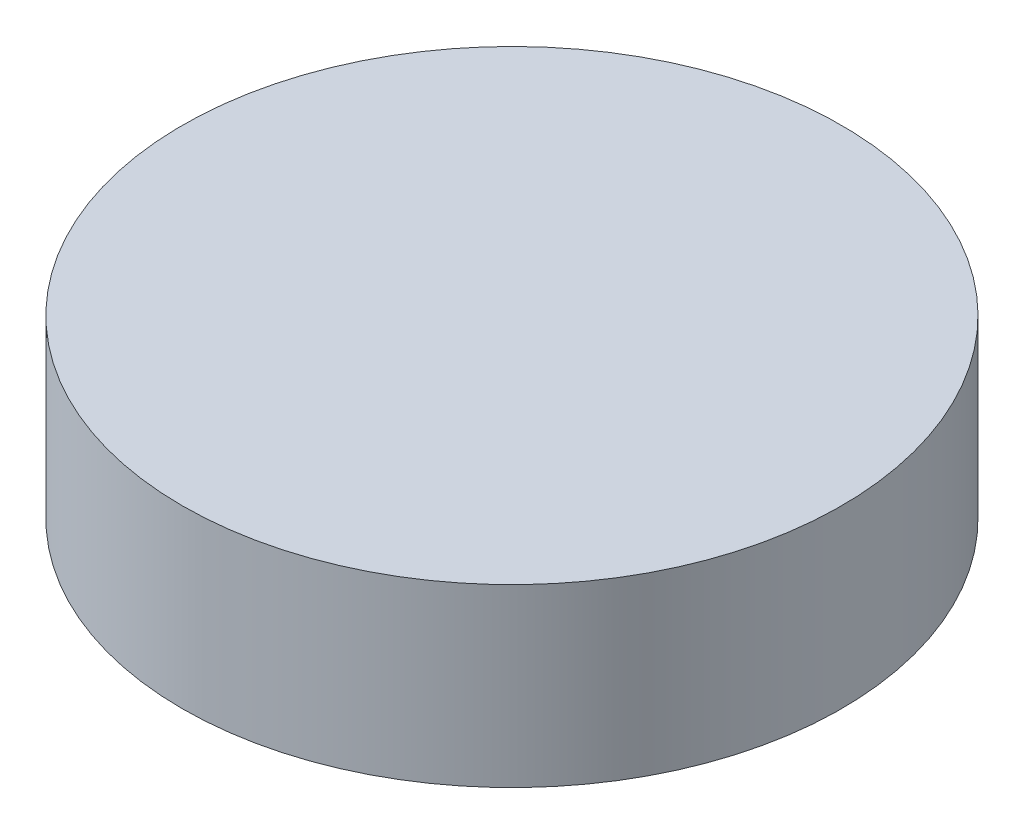
SolidWorks part; units mm, degrees
ref_plane "Front Plane" through (0, 0, 0) normal (0, 0, 1) x (1, 0, 0)
ref_plane "Top Plane" through (0, 0, 0) normal (0, 1, 0) x (1, 0, 0)
ref_plane "Right Plane" through (0, 0, 0) normal (1, 0, 0) x (0, 0, -1)
sketch "Sketch1" plane through (0, 0, 0) normal (0, 1, 0) x (1, 0, 0)
  circle A0 centre (0, 0) radius 3
  dimension "D1" = 6
extrude "Boss-Extrude1" add sketch "Sketch1" along normal blind 1.6
